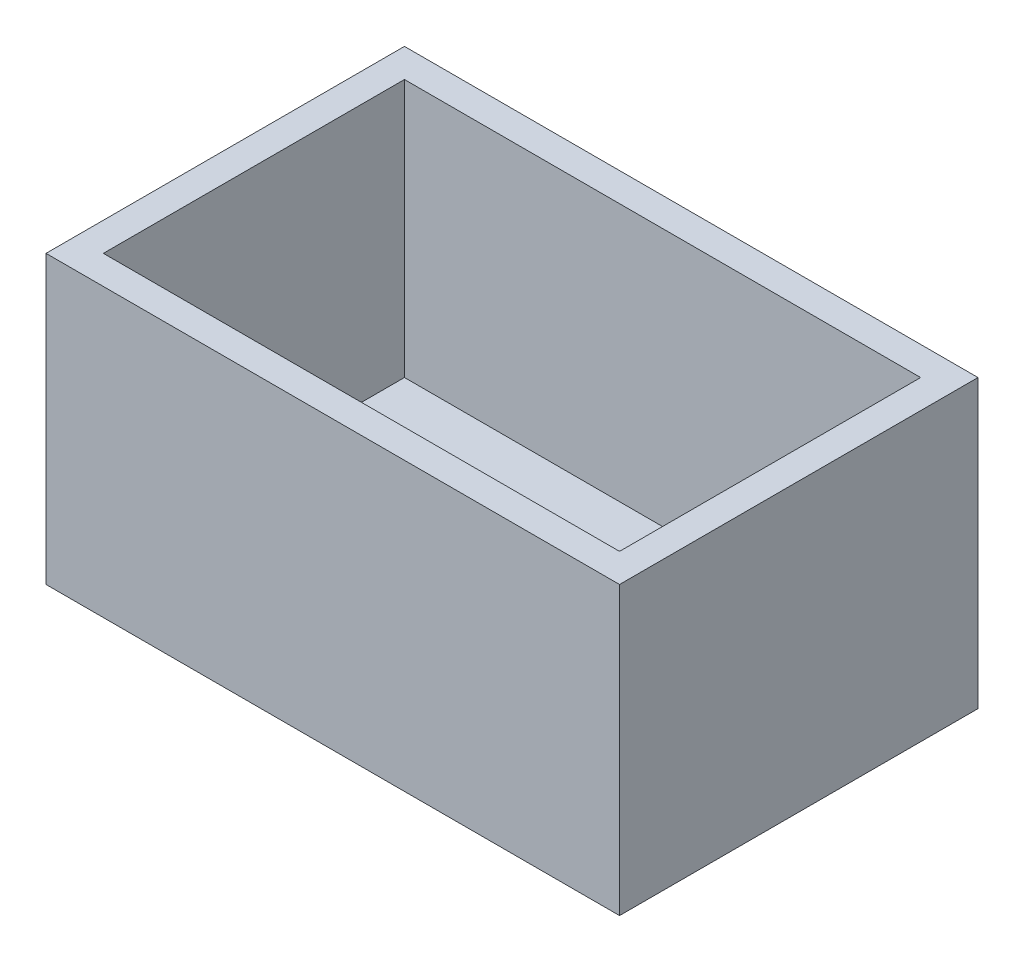
SolidWorks part; units mm, degrees
ref_plane "前视基准面" through (0, 0, 0) normal (0, 0, 1) x (1, 0, 0)
ref_plane "上视基准面" through (0, 0, 0) normal (0, 1, 0) x (1, 0, 0)
ref_plane "右视基准面" through (0, 0, 0) normal (1, 0, 0) x (0, 0, -1)
sketch "草图1" plane through (0, 0, 0) normal (0, 1, 0) x (1, 0, 0)
  line L0 (-40, 25) -> (40, 25)
  line L1 (40, 25) -> (40, -25)
  line L2 (40, -25) -> (-40, -25)
  line L3 (-40, -25) -> (-40, 25)
extrude "凸台-拉伸1" add sketch "草图1" along normal blind 40
shell "抽壳1" thickness 4
